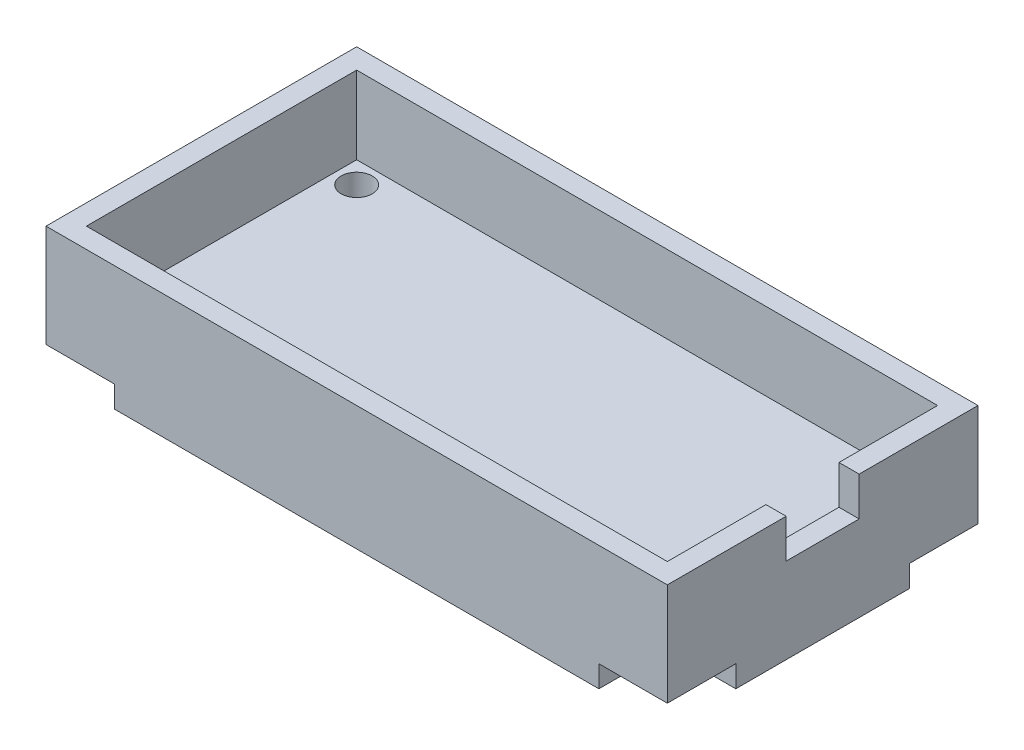
SolidWorks part; units mm, degrees
ref_plane "Face" through (0, 0, 0) normal (0, 0, 1) x (1, 0, 0)
ref_plane "Dessus" through (0, 0, 0) normal (0, 1, 0) x (1, 0, 0)
ref_plane "Droite" through (0, 0, 0) normal (1, 0, 0) x (0, 0, -1)
sketch "Esquisse1" plane through (0, 0, 0) normal (0, 0, 1) x (1, 0, 0)
  line L1 (0, 8) -> (40, 8)
  line L2 (0, 8) -> (0, 0)
  line L3 (0, 0) -> (40, 0)
  line L4 (40, 8) -> (40, 0)
  dimension "D1" = 40
  dimension "D2" = 8
extrude "Extrusion1" add sketch "Esquisse1" along normal mid plane 20
sketch "Esquisse2" plane through (0, 8, 0) normal (0, 1, 0) x (-1, 0, 0)
  line L0 (-41.4006, 0) -> (2.8198, 0) construction
  line L1 (-38.7, -8.7) -> (-1.3, -8.7)
  line L2 (-38.7, -8.7) -> (-38.7, 8.7)
  line L3 (-38.7, 8.7) -> (-1.3, 8.7)
  line L4 (-1.3, -8.7) -> (-1.3, 8.7)
  line L5 (-20, -24.6499) -> (-20, 21.0167) construction
  line L6 (-40, 10) -> (-40, -10) construction
  line L7 (0, 10) -> (0, -10) construction
  line L8 (-40, 10) -> (0, 10) construction
  line L9 (-40, -10) -> (0, -10) construction
  dimension "D1" = 1.3
  dimension "D2" = 1.3
extrude "Enlèv. mat.-Extru.1" cut sketch "Esquisse2" against normal blind 5
sketch "Esquisse3" plane through (0, 8, 0) normal (0, 1, 0) x (-1, 0, 0)
  line L0 (-22.4276, 0) -> (-17.6, 0) construction
  line L1 (-40, -2.35) -> (-38.7, -2.35)
  line L2 (-40, -2.35) -> (-40, 2.35)
  line L3 (-40, 2.35) -> (-38.7, 2.35)
  line L4 (-38.7, -2.35) -> (-38.7, 2.35)
  line L5 (-40, 10) -> (0, 10) construction
  line L6 (-40, -10) -> (0, -10) construction
  line L7 (-40, 10) -> (-40, -10) construction
  line L8 (-38.7, 8.7) -> (-38.7, -8.7) construction
  dimension "D1" = 4.7
extrude "Enlèv. mat.-Extru.2" cut sketch "Esquisse3" against normal blind 2.5
sketch "Esquisse4" plane through (0, 0, 0) normal (0, -1, 0) x (1, 0, 0)
  line L0 (41.55, 0) -> (-1.5877, 0) construction
  line L1 (20, 17.479) -> (20, -19.6452) construction
  line L2 (40, 10) -> (40, -10) construction
  line L3 (0, 10) -> (0, -10) construction
  line L4 (0, -10) -> (40, -10) construction
  line L5 (0, 10) -> (40, 10) construction
  circle A0 centre (37.3, 7.3) radius 1
  circle A1 centre (37.3, -7.3) radius 1
  circle A2 centre (2.7, -7.3) radius 1
  circle A3 centre (2.7, 7.3) radius 1
  dimension "D2" = 2
  dimension "D1" = 2.7
  dimension "D3" = 2.7
extrude "Enlèv. mat.-Extru.3" cut sketch "Esquisse4" against normal through all
sketch "Esquisse5" plane through (0, 0, 0) normal (0, -1, 0) x (1, 0, 0)
  line L0 (42.2222, 0) -> (-1.1338, 0) construction
  line L1 (20, 19.6452) -> (20, -25.8747) construction
  line L2 (40, 10) -> (40, -10) construction
  line L3 (0, 10) -> (0, -10) construction
  line L4 (0, -10) -> (40, -10) construction
  line L5 (0, 10) -> (40, 10) construction
  line L6 (40, -5.5929) -> (36.5929, -5.5929)
  line L7 (35.5929, -6.5929) -> (35.5929, -10)
  line L8 (35.5929, -10) -> (40, -10)
  line L9 (40, -10) -> (40, -5.5929)
  line L10 (40, 10) -> (40, 5.5929)
  line L11 (35.5929, 10) -> (40, 10)
  line L12 (35.5929, 6.5929) -> (35.5929, 10)
  line L13 (40, 5.5929) -> (36.5929, 5.5929)
  line L14 (0, 5.5929) -> (3.4071, 5.5929)
  line L15 (4.4071, 6.5929) -> (4.4071, 10)
  line L16 (4.4071, 10) -> (0, 10)
  line L17 (0, 10) -> (0, 5.5929)
  line L18 (0, -10) -> (0, -5.5929)
  line L19 (4.4071, -10) -> (0, -10)
  line L20 (4.4071, -6.5929) -> (4.4071, -10)
  line L21 (0, -5.5929) -> (3.4071, -5.5929)
  arc A0 (36.5929, -5.5929) -> (35.5929, -6.5929) centre (36.5929, -6.5929) ccw
  circle A2 centre (37.3, -7.3) radius 1 construction
  arc A3 (36.5929, 5.5929) -> (35.5929, 6.5929) centre (36.5929, 6.5929) cw
  arc A4 (3.4071, 5.5929) -> (4.4071, 6.5929) centre (3.4071, 6.5929) ccw
  arc A5 (3.4071, -5.5929) -> (4.4071, -6.5929) centre (3.4071, -6.5929) cw
extrude "Enlèv. mat.-Extru.4" cut sketch "Esquisse5" against normal blind 1.4
